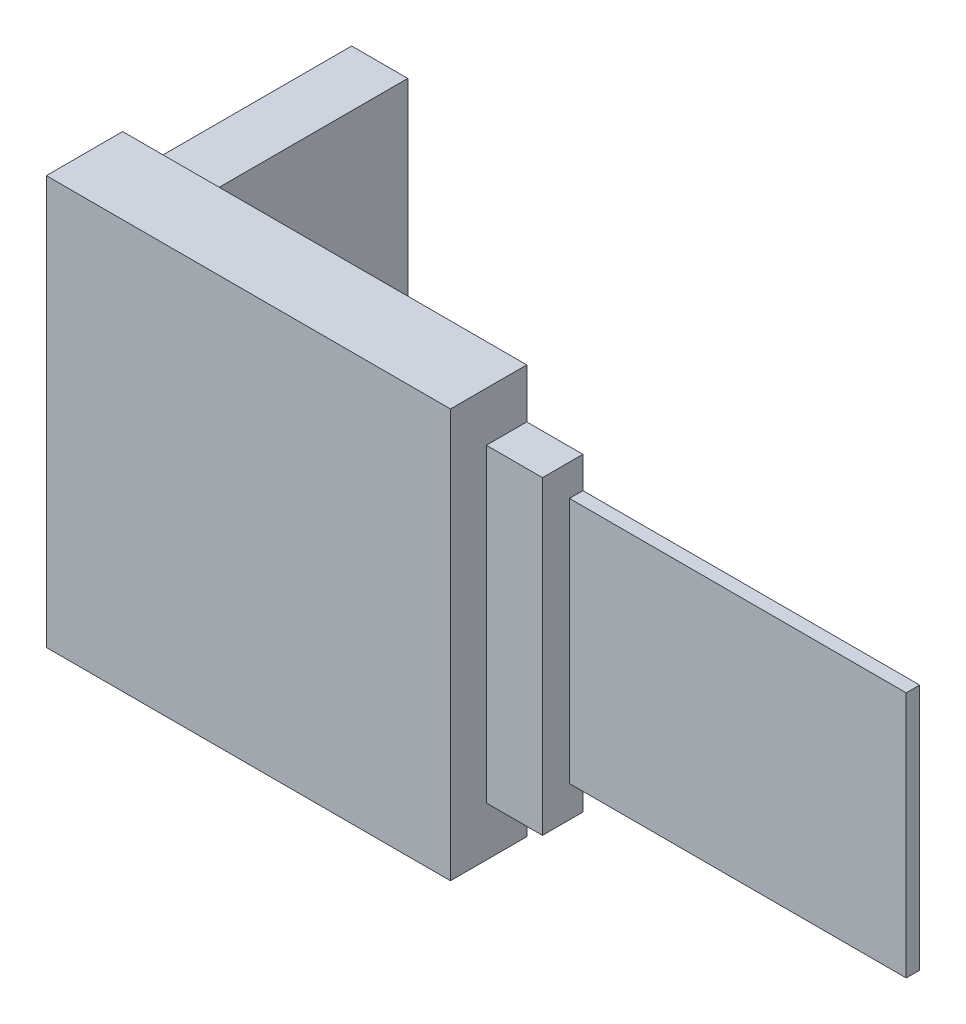
SolidWorks part; units mm, degrees
ref_plane "前基準面" through (0, 0, 0) normal (0, 0, 1) x (1, 0, 0)
ref_plane "上基準面" through (0, 0, 0) normal (0, 1, 0) x (1, 0, 0)
ref_plane "右基準面" through (0, 0, 0) normal (1, 0, 0) x (0, 0, -1)
sketch "草圖1" plane through (0, 0, 0) normal (0, 0, 1) x (1, 0, 0)
  line L0 (-52.3345, -91.7074) -> (-50.2423, -91.7074) construction
  line L1 (-48.0345, -68.5074) -> (-30.0345, -68.5074)
  line L2 (-48.0345, -68.5074) -> (-48.0345, -86.7074)
  line L3 (-48.0345, -86.7074) -> (-30.0345, -86.7074)
  line L4 (-30.0345, -68.5074) -> (-30.0345, -86.7074)
  line L5 (-53.0345, -48.4074) -> (-53.0345, -91.0074) construction
  dimension "D1" = 18
  dimension "D2" = 18.2
  dimension "D3" = 5
  dimension "D4" = 5
extrude "填料-伸長1" add sketch "草圖1" along normal blind 3.4
sketch "草圖2" plane through (0, 0, 0) normal (0, 0, -1) x (-1, 0, 0)
  line L0 (48.0345, -86.7074) -> (30.0345, -86.7074) construction
  line L1 (47.8345, -85.1074) -> (45.3345, -85.1074)
  line L2 (47.8345, -85.1074) -> (47.8345, -70.1074)
  line L3 (47.8345, -70.1074) -> (45.3345, -70.1074)
  line L4 (45.3345, -85.1074) -> (45.3345, -70.1074)
  line L5 (30.0345, -68.5074) -> (48.0345, -68.5074) construction
  line L6 (48.0345, -68.5074) -> (48.0345, -86.7074) construction
  point P6 (46.5845, -85.1074)
  dimension "D1" = 2.5
  dimension "D2" = 15
  dimension "D3" = 1.6
  dimension "D4" = 1.6
  dimension "D5" = 0.2
extrude "填料-伸長2" add sketch "草圖2" along normal blind 10
sketch "草圖3" plane through (0, 0, 0) normal (0, 0, -1) x (-1, 0, 0)
  line L0 (30.0345, -86.7074) -> (30.0345, -68.5074) construction
  line L1 (27.5345, -84.5074) -> (30.0345, -84.5074)
  line L2 (27.5345, -84.5074) -> (27.5345, -70.7074)
  line L3 (27.5345, -70.7074) -> (30.0345, -70.7074)
  line L4 (30.0345, -84.5074) -> (30.0345, -70.7074)
  line L5 (30.0345, -68.5074) -> (48.0345, -68.5074) construction
  line L6 (48.0345, -86.7074) -> (30.0345, -86.7074) construction
  point P8 (30.0345, -77.6074)
  dimension "D1" = 2.5
  dimension "D2" = 13.8
  dimension "D3" = 9.1
  dimension "D4" = 9.1
extrude "填料-伸長3" add sketch "草圖3" against normal blind 1.8
sketch "草圖4" plane through (0, 0, 0) normal (0, 0, -1) x (-1, 0, 0)
  line L6 (12.5345, -72.1074) -> (27.5345, -72.1074)
  line L7 (12.5345, -72.1074) -> (12.5345, -83.1074)
  line L8 (12.5345, -83.1074) -> (27.5345, -83.1074)
  line L9 (27.5345, -72.1074) -> (27.5345, -83.1074)
  line L11 (27.5345, -70.7074) -> (27.5345, -84.5074) construction
  dimension "D1" = 15
  dimension "D2" = 11
extrude "填料-伸長4" add sketch "草圖4" against normal blind 0.6
